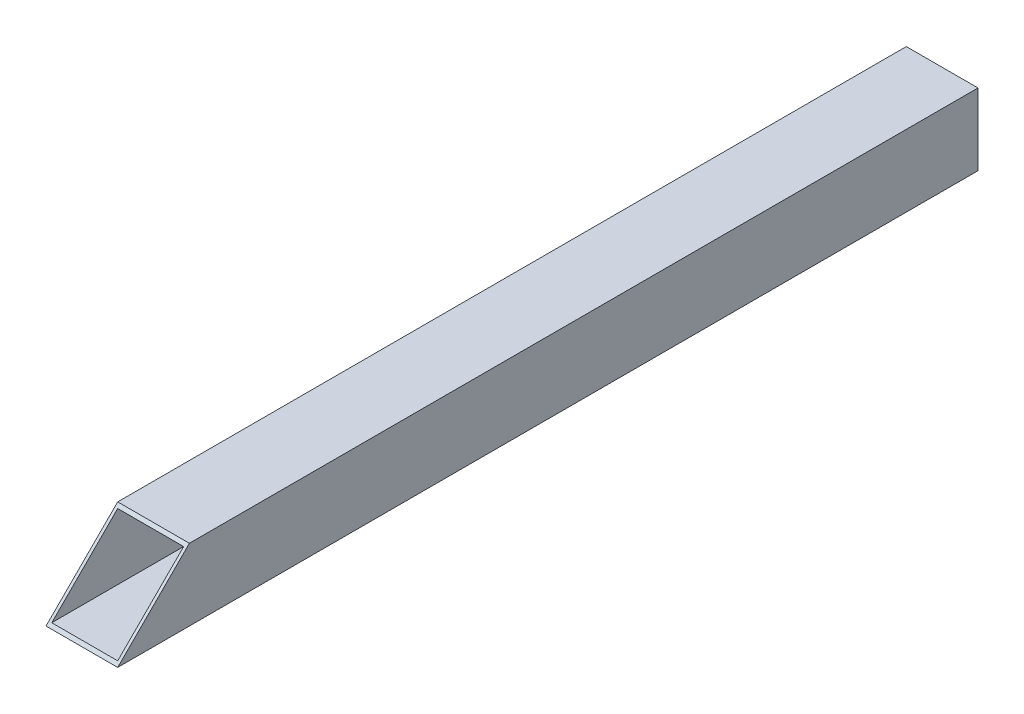
SolidWorks part; units mm, degrees
ref_plane "Front Plane" through (0, 0, 0) normal (0, 0, 1) x (1, 0, 0)
ref_plane "Top Plane" through (0, 0, 0) normal (0, 1, 0) x (1, 0, 0)
ref_plane "Right Plane" through (0, 0, 0) normal (1, 0, 0) x (0, 0, -1)
sketch "Sketch1" plane through (0, 0, 0) normal (0, 0, 1) x (1, 0, 0)
  line L0 (-11.5, -11.5) -> (11.5, -11.5)
  line L1 (-12.5, -12.5) -> (12.5, -12.5)
  line L2 (-12.5, -12.5) -> (-12.5, 12.5)
  line L3 (-12.5, 12.5) -> (12.5, 12.5)
  line L4 (12.5, -12.5) -> (12.5, 12.5)
  line L5 (-12.5, -12.5) -> (12.5, 12.5) construction
  line L6 (-12.5, 12.5) -> (12.5, -12.5) construction
  line L7 (11.5, -11.5) -> (11.5, 11.5)
  line L8 (-11.5, 11.5) -> (11.5, 11.5)
  line L9 (-11.5, -11.5) -> (-11.5, 11.5)
  point P0 (0, 0)
  dimension "D1" = 25
  dimension "D2" = 1
extrude "Boss-Extrude1" add sketch "Sketch1" along normal blind 300
sketch "Sketch2" plane through (12.5, 0, 0) normal (1, 0, 0) x (0, 0, -1)
  line L0 (-300, -12.5) -> (-275, 12.5)
  line L1 (-300, 12.5) -> (0, 12.5) construction
  line L2 (-275, 12.5) -> (-300, 12.5)
  line L3 (-300, 12.5) -> (-300, -12.5)
  dimension "D1" = 45
extrude "Cut-Extrude1" cut sketch "Sketch2" against normal through all
